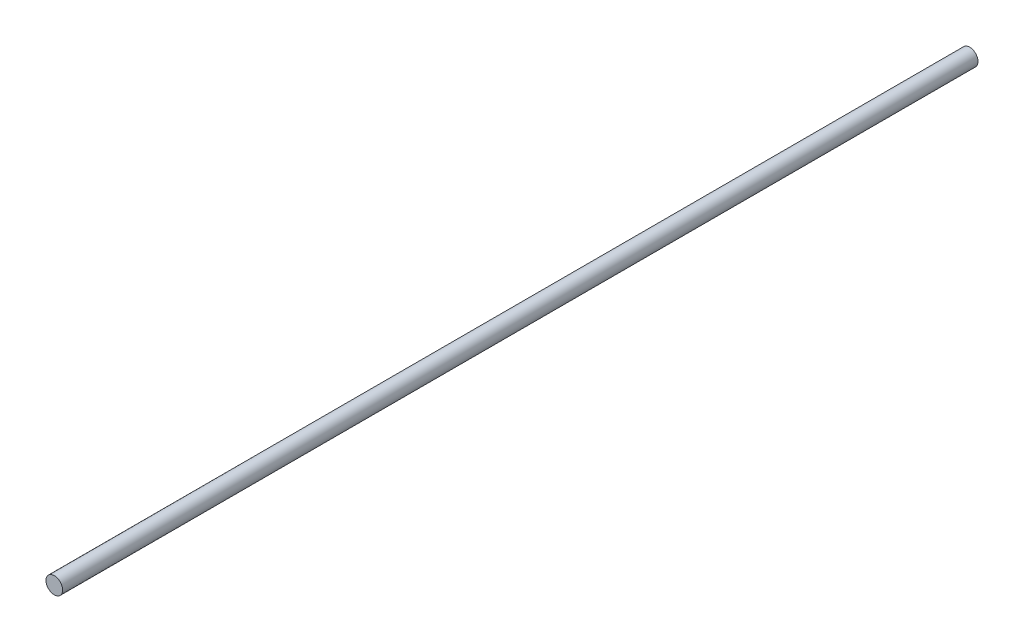
SolidWorks part; units mm, degrees
ref_plane "Płaszczyzna przednia" through (0, 0, 0) normal (0, 0, 1) x (1, 0, 0)
ref_plane "Płaszczyzna górna" through (0, 0, 0) normal (0, 1, 0) x (1, 0, 0)
ref_plane "Płaszczyzna prawa" through (0, 0, 0) normal (1, 0, 0) x (0, 0, -1)
sketch "Szkic1" plane through (0, 0, 0) normal (0, 0, 1) x (1, 0, 0)
  circle A0 centre (0, 0) radius 4
extrude "Dodanie-wyciągnięcie1" add sketch "Szkic1" along normal blind 440
